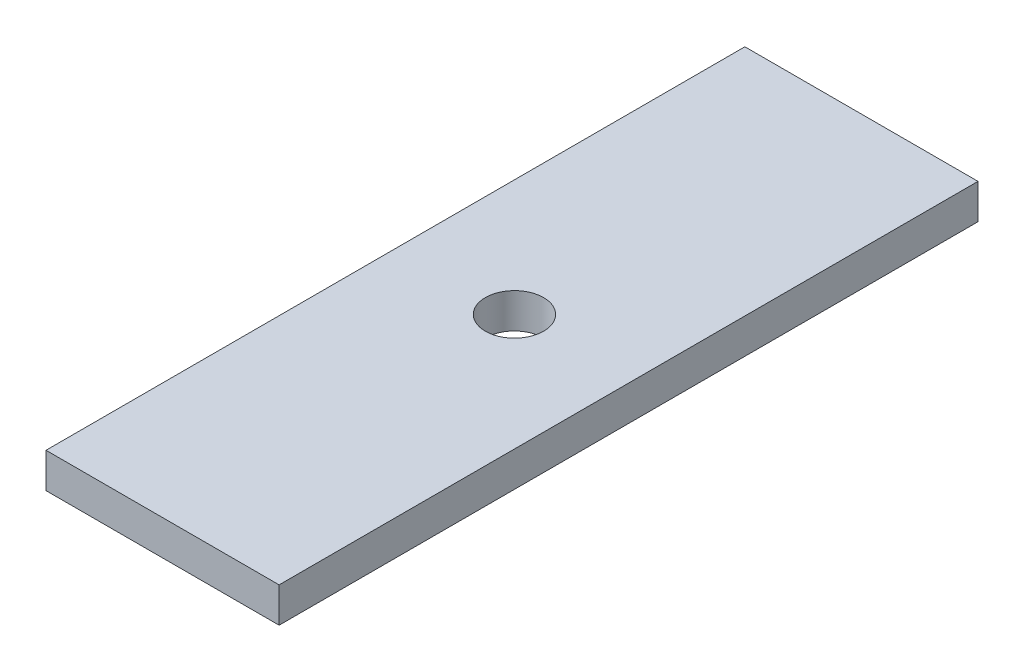
SolidWorks part; units mm, degrees
ref_plane "Front Plane" through (0, 0, 0) normal (0, 0, 1) x (1, 0, 0)
ref_plane "Top Plane" through (0, 0, 0) normal (0, 1, 0) x (1, 0, 0)
ref_plane "Right Plane" through (0, 0, 0) normal (1, 0, 0) x (0, 0, -1)
sketch "Sketch1" plane through (0, 0, 0) normal (0, 1, 0) x (1, 0, 0)
  line L1 (-10, -29.9793) -> (10, -29.9793)
  line L2 (-10, -29.9793) -> (-10, 29.9793)
  line L3 (-10, 29.9793) -> (10, 29.9793)
  line L4 (10, -29.9793) -> (10, 29.9793)
  line L5 (-10, -29.9793) -> (10, 29.9793) construction
  line L6 (-10, 29.9793) -> (10, -29.9793) construction
  circle A0 centre (0, 0.21) radius 2.5
  point P0 (0, 0)
  dimension "D3" = 5
  dimension "D1" = 59.9587
  dimension "D2" = 20
extrude "Boss-Extrude1" add sketch "Sketch1" along normal blind 3
